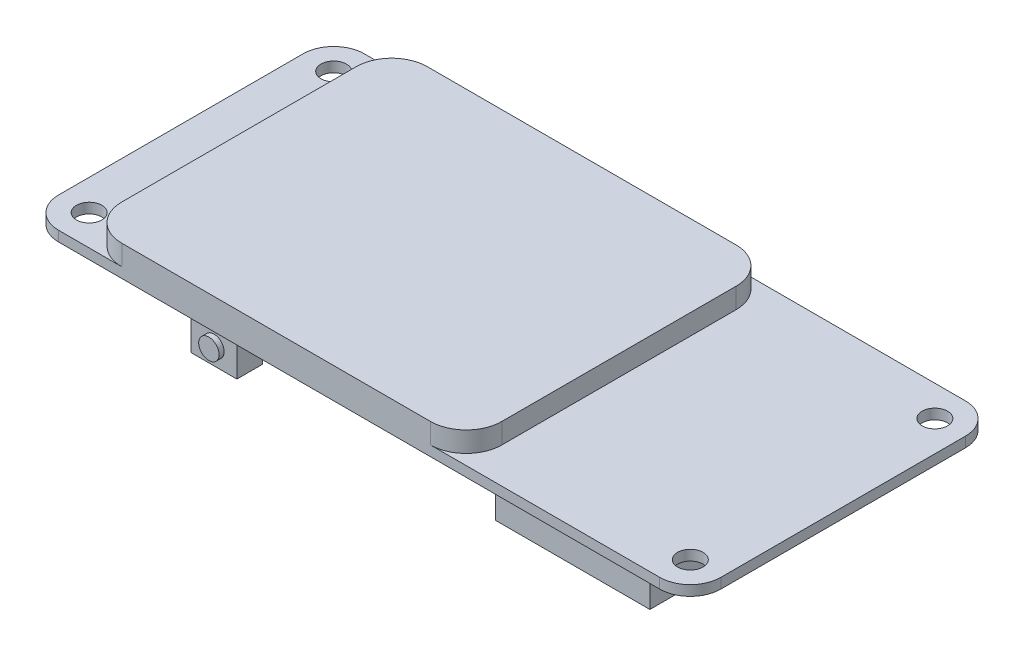
SolidWorks part; units mm, degrees
ref_plane "前视基准面" through (0, 0, 0) normal (0, 0, 1) x (1, 0, 0)
ref_plane "上视基准面" through (0, 0, 0) normal (0, 1, 0) x (1, 0, 0)
ref_plane "右视基准面" through (0, 0, 0) normal (1, 0, 0) x (0, 0, -1)
other "Configuration Table"
sketch "草图1" plane through (0, 0, 0) normal (0, 1, 0) x (1, 0, 0)
  line L1 (-29.5, 15) -> (29.5, 15)
  line L2 (-32.5, 12) -> (-32.5, -12)
  line L3 (-29.5, -15) -> (29.5, -15)
  line L4 (32.5, 12) -> (32.5, -12)
  line L5 (-32.5, 15) -> (32.5, -15) construction
  line L6 (-32.5, -15) -> (32.5, 15) construction
  arc A0 (29.5, -15) -> (32.5, -12) centre (29.5, -12) ccw
  arc A1 (29.5, 15) -> (32.5, 12) centre (29.5, 12) cw
  arc A2 (-32.5, -12) -> (-29.5, -15) centre (-29.5, -12) ccw
  arc A3 (-29.5, 15) -> (-32.5, 12) centre (-29.5, 12) ccw
  circle A4 centre (-29.5, 12) radius 1.25
  circle A5 centre (29.5, 12) radius 1.25
  circle A6 centre (-29.5, -12) radius 1.25
  circle A7 centre (29.5, -12) radius 1.25
  point P0 (0, 0)
  dimension "D3" = 3
  dimension "D4" = 2.5
  dimension "D1" = 65
  dimension "D2" = 30
extrude "board" add sketch "草图1" along normal blind 1
sketch "草图2" plane through (0, 1, 0) normal (0, 1, 0) x (1, 0, 0)
  line L0 (29.5, 15) -> (-29.5, 15) construction
  line L1 (-26.8, 15) -> (10.5, 15)
  line L2 (-26.8, 15) -> (-26.8, -15)
  line L3 (-26.8, -15) -> (10.5, -15)
  line L4 (10.5, 15) -> (10.5, -15)
  line L5 (-29.5, -15) -> (29.5, -15) construction
  line L6 (-32.5, 12) -> (-32.5, -12) construction
  line L7 (32.5, -12) -> (32.5, 12) construction
  point P8 (0, 0)
  point P10 (-35.2312, 11.6088)
  point P11 (-32.5, 9.179)
  dimension "D1" = 22
  dimension "D2" = 5.7
extrude "screen" add sketch "草图2" along normal blind 2
fillet "screen-radius" radius 3.5 4 edges at (-26.8, 2, -15) (10.5, 2, -15) (10.5, 2, 15) (-26.8, 2, 15)
sketch "草图3" plane through (0, 0, 0) normal (0, -1, 0) x (1, 0, 0)
  line L0 (32.5, 12) -> (32.5, -12) construction
  line L1 (-25.5, -9) -> (25.5, -9)
  line L2 (-25.5, -9) -> (-25.5, -14)
  line L3 (-25.5, -14) -> (25.5, -14)
  line L4 (25.5, -9) -> (25.5, -14)
  line L6 (29.5, -15) -> (-29.5, -15) construction
  point P6 (31.8566, -0.7424)
  point P7 (31.2492, -8.5716)
  point P10 (20.5178, -16.2658)
  dimension "D1" = 5
  dimension "D2" = 51
  dimension "D3" = 7
  dimension "D4" = 1
extrude "plug" add sketch "草图3" along normal blind 7
sketch "草图4" plane through (0, 0, 0) normal (0, -1, 0) x (1, 0, 0)
  line L0 (32.5, 12) -> (32.5, -12) construction
  line L1 (10.61, 12.2162) -> (25.75, 12.2162)
  line L2 (10.61, 12.2162) -> (10.61, -7.7838)
  line L3 (10.61, -7.7838) -> (25.75, -7.7838)
  line L4 (25.75, 12.2162) -> (25.75, -7.7838)
  point P6 (31.3841, 6.8843)
  dimension "D1" = 15.14
  dimension "D2" = 20
  dimension "D3" = 6.75
extrude "speaker" add sketch "草图4" along normal blind 5
sketch "草图5" plane through (0, 0, 0) normal (0, -1, 0) x (1, 0, 0)
  line L0 (-29.5, 15) -> (29.5, 15) construction
  line L1 (-17, 14.5) -> (-12.5, 14.5)
  line L2 (-17, 14.5) -> (-17, 12)
  line L3 (-17, 12) -> (-12.5, 12)
  line L4 (-12.5, 14.5) -> (-12.5, 12)
  line L5 (-32.5, -12) -> (-32.5, 12) construction
  point P4 (-13.701, 13.6944)
  dimension "D1" = 4.5
  dimension "D2" = 2.5
  dimension "D3" = 0.5
  dimension "D4" = 15.5
extrude "button" add sketch "草图5" along normal blind 3.4
sketch "草图6" plane through (0, 0, 14.5) normal (0, 0, 1) x (1, 0, 0)
  line L0 (-12.5, 0) -> (-17, 0) construction
  line L1 (-12.5, -3.4) -> (-17, -3.4) construction
  circle A0 centre (-14.75, -1.7) radius 1
  point P4 (0, 0)
  point P7 (-14.75, -3.4)
  dimension "D1" = 2
  dimension "D2" = 1.7
extrude "button-tap" add sketch "草图6" along normal blind 0.5
